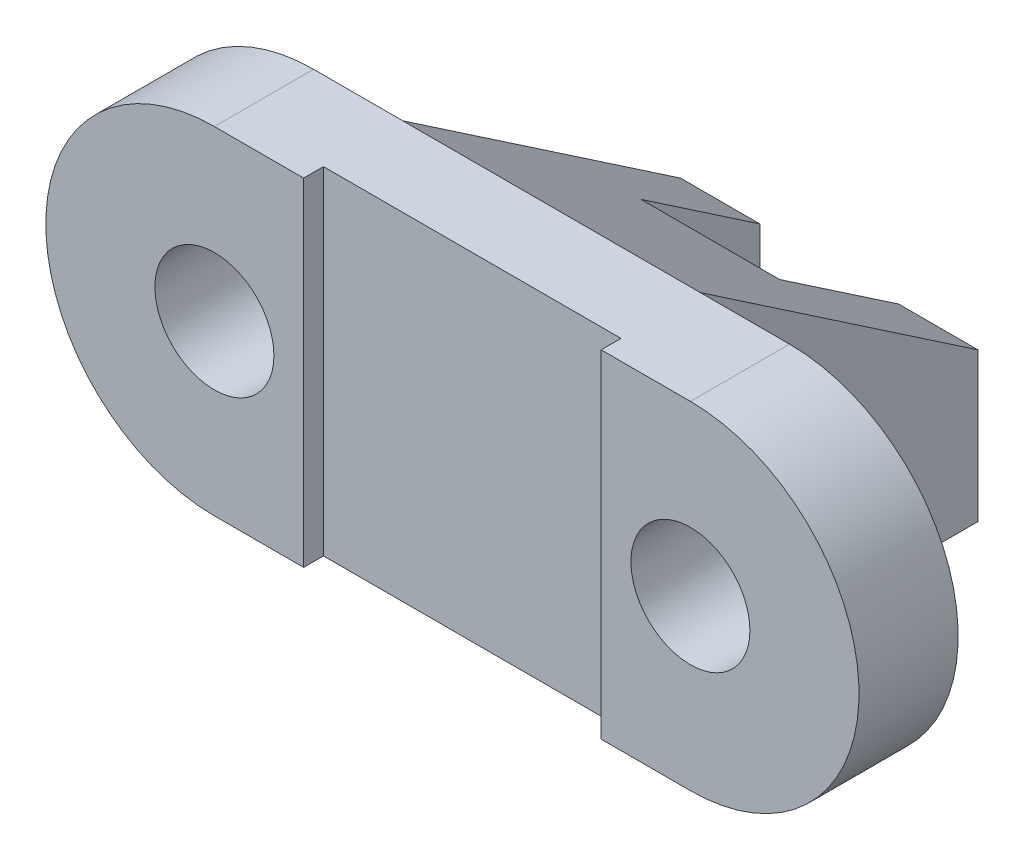
SolidWorks part; units mm, degrees
ref_plane "前视基准面" through (0, 0, 0) normal (0, 0, 1) x (1, 0, 0)
ref_plane "上视基准面" through (0, 0, 0) normal (0, 1, 0) x (1, 0, 0)
ref_plane "右视基准面" through (0, 0, 0) normal (1, 0, 0) x (0, 0, -1)
other "Configuration Table"
sketch "草图1" plane through (0, 0, 0) normal (0, 0, 1) x (1, 0, 0)
  line L1 (24, -17) -> (-24, -17)
  line L3 (24, 17) -> (-24, 17)
  line L5 (24, -17) -> (-24, 17) construction
  line L6 (24, 17) -> (-24, -17) construction
  arc A0 (-24, 17) -> (-24, -17) centre (-24, 0) ccw
  arc A1 (24, 17) -> (24, -17) centre (24, 0) cw
  point P0 (0, 0)
  dimension "D1" = 48
  dimension "D2" = 34
extrude "凸台-拉伸1" add sketch "草图1" along normal blind 10
sketch "草图2" plane through (0, 0, 0) normal (0, 0, 1) x (1, 0, 0)
  circle A1 centre (-24, 0) radius 6
  circle A2 centre (24, 0) radius 6
extrude "切除-拉伸1" cut sketch "草图2" along normal blind 18
sketch "草图3" plane through (0, 0, 0) normal (0, 0, 1) x (1, 0, 0)
  line L1 (-15, -17) -> (15, -17)
  line L2 (-15, -17) -> (-15, 17)
  line L3 (-15, 17) -> (15, 17)
  line L4 (15, -17) -> (15, 17)
  line L5 (-15, -17) -> (15, 17) construction
  line L6 (-15, 17) -> (15, -17) construction
  point P0 (0, 0)
  dimension "D1" = 30
  dimension "D2" = 34
extrude "凸台-拉伸2" add sketch "草图3" against normal blind 28
sketch "草图4" plane through (0, -17, 0) normal (0, -1, 0) x (1, 0, 0)
  line L0 (-15, -28) -> (15, -28) construction
  line L1 (7, -40) -> (-7, -40)
  line L2 (7, -40) -> (7, -16)
  line L3 (7, -16) -> (-7, -16)
  line L4 (-7, -40) -> (-7, -16)
  line L5 (7, -40) -> (-7, -16) construction
  line L6 (7, -16) -> (-7, -40) construction
  point P0 (0, -28)
  dimension "D1" = 14
  dimension "D2" = 24
extrude "切除-拉伸2" cut sketch "草图4" against normal blind 45 and the other way blind 14
sketch "草图5" plane through (-15, 0, 0) normal (-1, 0, 0) x (0, 0, 1)
  line L0 (0, 17) -> (-28, 17)
  line L1 (-28, 17) -> (-28, -2)
  line L2 (-28, 17) -> (-28, -17) construction
  line L3 (-28, -2) -> (0, 17)
  dimension "D1" = 19
extrude "切除-拉伸3" cut sketch "草图5" against normal blind 45
sketch "草图6" plane through (0, 17, 0) normal (0, 1, 0) x (1, 0, 0)
  line L0 (24, -10) -> (-24, -10) construction
  line L1 (-15, -8) -> (15, -8)
  line L2 (-15, -8) -> (-15, -12)
  line L3 (-15, -12) -> (15, -12)
  line L4 (15, -8) -> (15, -12)
  line L5 (-15, -8) -> (15, -12) construction
  line L6 (-15, -12) -> (15, -8) construction
  point P0 (0, -10)
  dimension "D1" = 2
  dimension "30" = 30
extrude "切除-拉伸5" cut sketch "草图6" against normal up to surface (34 mm away) up to face at (0, -17, -10.3333)
